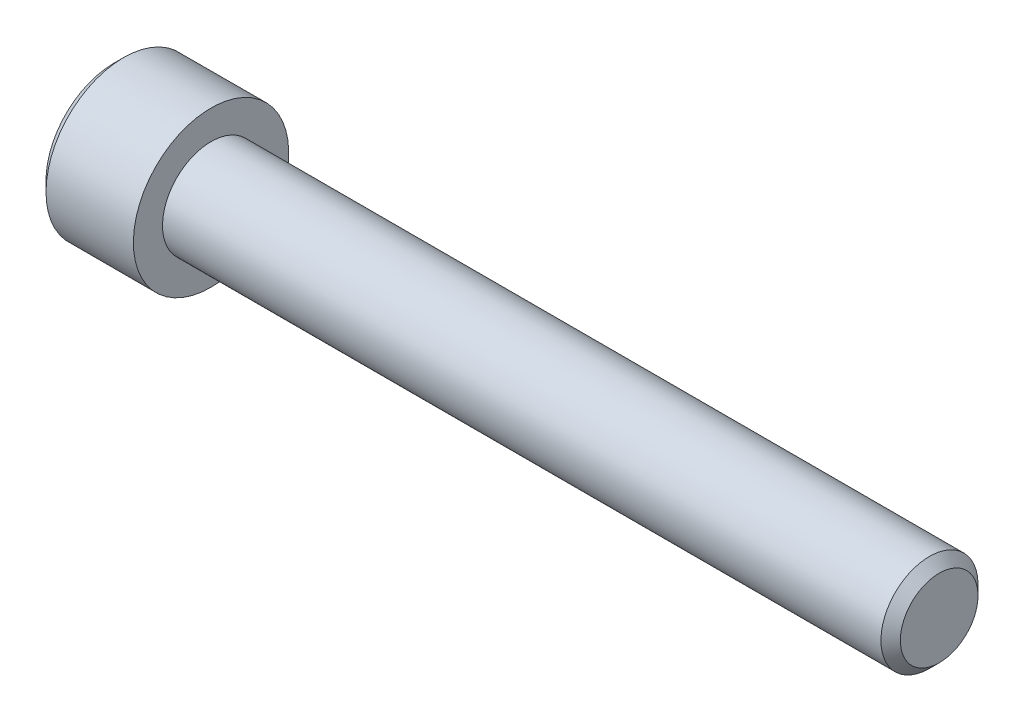
SolidWorks part; units mm, degrees
ref_plane "Front" through (0, 0, 0) normal (0, 0, 1) x (1, 0, 0)
ref_plane "Top" through (0, 0, 0) normal (0, 1, 0) x (1, 0, 0)
ref_plane "Right" through (0, 0, 0) normal (1, 0, 0) x (0, 0, -1)
sketch "Sketch1" plane through (0, 0, 0) normal (0, 0, 1) x (1, 0, 0)
  line L0 (-10, 0) -> (-10, 8)
  line L1 (-10, 0) -> (75, 0)
  line L2 (-10, 8) -> (0, 8)
  line L3 (0, 8) -> (0, 5)
  line L4 (0, 5) -> (75, 5)
  line L6 (75, 5) -> (75, 0)
  line L8 (75, 0) -> (-10, 0) construction
  dimension "D1" = 16
  dimension "D2" = 10
  dimension "D3" = 10
  dimension "D4" = 75
revolve "Revolve1" add sketch "Sketch1" angle 360 about L8
cosmetic thread "Cosmetic Thread1" parameters "D2"=8.619
sketch "Sketch2" plane through (0, 0, 0) normal (0, 0, 1) x (1, 0, 0)
  line L0 (-10, 0) -> (-10, 3.995)
  line L1 (-10, 3.995) -> (-5, 3.995)
  line L2 (-5, 3.995) -> (-3.9295, 0)
  line L3 (-10, 8) -> (-10, -8) construction
  line L4 (-3.9295, 0) -> (-10, 0) construction
  line L5 (-10, 0) -> (-3.9295, 0)
  dimension "D1" = 75
  dimension "D2" = 7.99
  dimension "D3" = 5
revolve "Cut-Revolve1" cut sketch "Sketch2" angle 360 about L4
sketch "Sketch3" plane through (-10, 0, 0) normal (1, 0, 0) x (0, 0, -1)
  line L1 (0, 4.6188) -> (-4, 2.3094)
  line L2 (-4, 2.3094) -> (-4, -2.3094)
  line L3 (-4, -2.3094) -> (0, -4.6188)
  line L4 (0, -4.6188) -> (4, -2.3094)
  line L5 (4, -2.3094) -> (4, 2.3094)
  line L6 (4, 2.3094) -> (0, 4.6188)
  circle A0 centre (0, 0) radius 4 construction
  dimension "D1" = 8
extrude "Cut-Extrude1" cut sketch "Sketch3" along normal blind 5
chamfer "Chamfer1" distance 1 angle 45 2 edges at (-10, -8, 0) (75, -5, 0)
